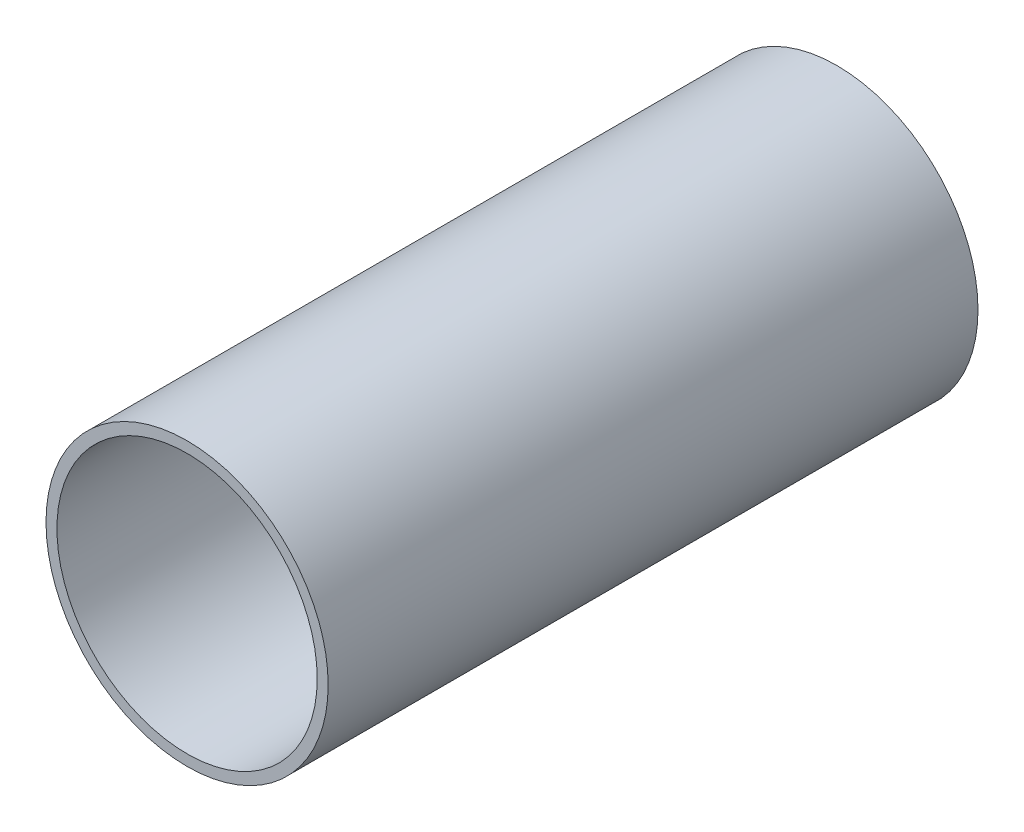
SolidWorks part; units mm, degrees
material "PE High Density"
ref_plane "Front Plane" through (0, 0, 0) normal (0, 0, 1) x (1, 0, 0)
ref_plane "Top Plane" through (0, 0, 0) normal (0, 1, 0) x (1, 0, 0)
ref_plane "Right Plane" through (0, 0, 0) normal (1, 0, 0) x (0, 0, -1)
sketch "Extrude sketch 1" plane through (0, 0, 0) normal (0, 0, 1) x (1, 0, 0)
  circle A0 centre (240, 0) radius 80
  circle A1 centre (240, 0) radius 73.8
  dimension "D1" = 147.6
  dimension "D2" = 160
extrude "Extrude 1" add sketch "Extrude sketch 1" along normal blind 368.5 from offset 60 separate body
